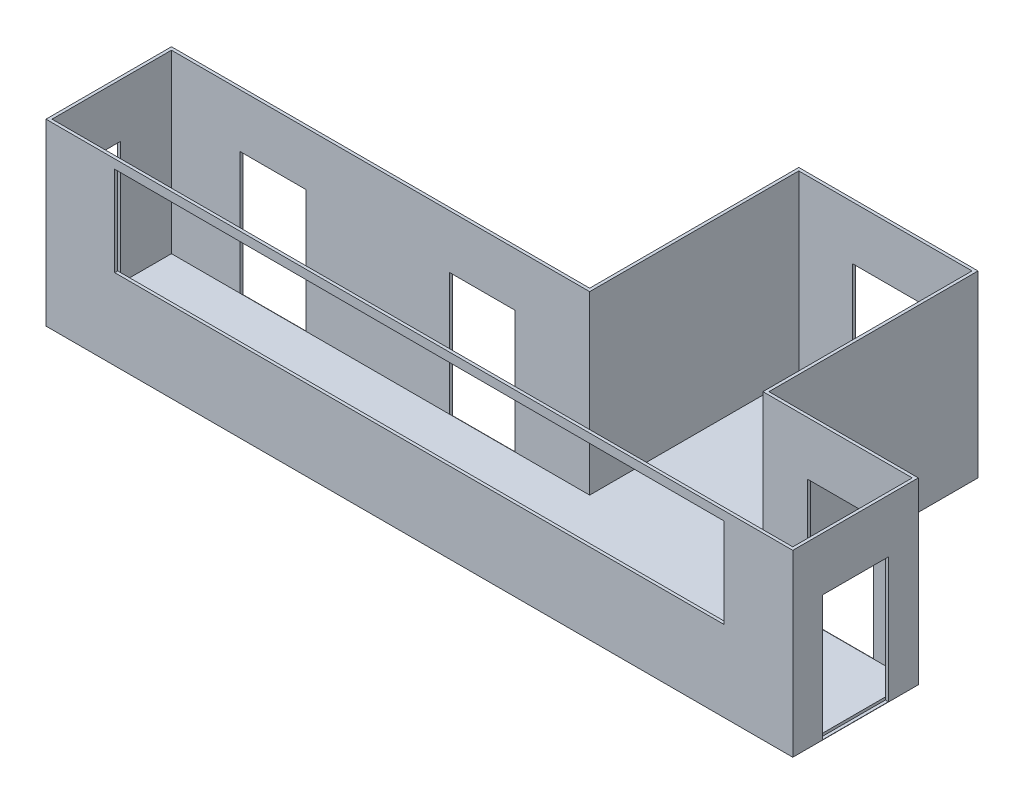
SolidWorks part; units mm, degrees
ref_plane "Front Plane" through (0, 0, 0) normal (0, 0, 1) x (1, 0, 0)
ref_plane "Top Plane" through (0, 0, 0) normal (0, 1, 0) x (1, 0, 0)
ref_plane "Right Plane" through (0, 0, 0) normal (1, 0, 0) x (0, 0, -1)
sketch "Sketch1" plane through (0, 0, 0) normal (0, 1, 0) x (1, 0, 0)
  line L0 (4377.6371, 49.5781) -> (6877.6371, 49.5781)
  line L1 (-5622.3629, 49.5781) -> (1377.6371, 49.5781)
  line L2 (-5622.3629, 49.5781) -> (-5622.3629, -2050.4219)
  line L3 (-5622.3629, -2050.4219) -> (6877.6371, -2050.4219)
  line L4 (6877.6371, 49.5781) -> (6877.6371, -2050.4219)
  line L5 (-5622.3629, 49.5781) -> (6877.6371, -2050.4219) construction
  line L6 (-5622.3629, -2050.4219) -> (6877.6371, 49.5781) construction
  line L7 (1377.6371, 3549.5781) -> (4377.6371, 3549.5781)
  line L8 (1377.6371, 3549.5781) -> (1377.6371, 49.5781)
  line L10 (4377.6371, 3549.5781) -> (4377.6371, 49.5781)
  line L11 (1377.6371, 3549.5781) -> (4377.6371, 49.5781) construction
  line L12 (1377.6371, 49.5781) -> (4377.6371, 3549.5781) construction
  point P4 (627.6371, -1000.4219)
  point P9 (2877.6371, 1799.5781)
  dimension "D1" = 12500
  dimension "D2" = 2100
  dimension "D3" = 7000
  dimension "D4" = 3000
  dimension "D5" = 3500
extrude "Boss-Extrude1" add sketch "Sketch1" along normal blind 3000
shell "Shell1" thickness 50
sketch "Sketch2" plane through (-5622.3629, 0, 0) normal (-1, 0, 0) x (0, 0, 1)
  line L0 (2050.4219, 3000) -> (2050.4219, 0) construction
  line L1 (850.4219, 2105) -> (1950.4219, 2105)
  line L2 (850.4219, 2105) -> (850.4219, 5)
  line L3 (850.4219, 5) -> (1950.4219, 5)
  line L4 (1950.4219, 2105) -> (1950.4219, 5)
  line L5 (850.4219, 2105) -> (1950.4219, 5) construction
  line L6 (850.4219, 5) -> (1950.4219, 2105) construction
  line L7 (-49.5781, 0) -> (2050.4219, 0) construction
  point P4 (1400.4219, 1055)
  dimension "D1" = 1100
  dimension "D2" = 100
  dimension "D3" = 2100
  dimension "D4" = 2105
extrude "Cut-Extrude1" cut sketch "Sketch2" against normal blind 50
sketch "Sketch3" plane through (0, 0, -49.5781) normal (0, 0, -1) x (-1, 0, 0)
  line L0 (5622.3629, 3000) -> (2122.3629, 3000)
  line L1 (-1377.6371, 3000) -> (5622.3629, 3000) construction
  line L2 (3872.3629, 3000) -> (3872.3629, 0) construction
  line L3 (-1377.6371, 0) -> (5622.3629, 0) construction
  line L4 (2122.3629, 3000) -> (-1377.6371, 3000)
  line L5 (4422.3629, 5) -> (3322.3629, 5)
  line L6 (4422.3629, 5) -> (4422.3629, 2105)
  line L7 (4422.3629, 2105) -> (3322.3629, 2105)
  line L8 (3322.3629, 5) -> (3322.3629, 2105)
  line L9 (4422.3629, 5) -> (3322.3629, 2105) construction
  line L10 (4422.3629, 2105) -> (3322.3629, 5) construction
  line L11 (372.3629, 3000) -> (372.3629, 0) construction
  line L13 (922.3629, 5) -> (-177.6371, 5)
  line L14 (922.3629, 5) -> (922.3629, 2105)
  line L15 (922.3629, 2105) -> (-177.6371, 2105)
  line L16 (-177.6371, 5) -> (-177.6371, 2105)
  line L17 (922.3629, 5) -> (-177.6371, 2105) construction
  line L18 (922.3629, 2105) -> (-177.6371, 5) construction
  point P9 (3872.3629, 1055)
  point P18 (372.3629, 1055)
  dimension "D1" = 3500
  dimension "D2" = 1100
  dimension "D3" = 2100
  dimension "D4" = 2105
  dimension "D5" = 2100
  dimension "D6" = 2105
  dimension "D7" = 1100
extrude "Cut-Extrude2" cut sketch "Sketch3" against normal blind 50 contours L16 L13 L14 L15 | L8 L5 L6 L7
sketch "Sketch4" plane through (0, 0, -3549.5781) normal (0, 0, -1) x (-1, 0, 0)
  line L0 (-2877.6371, 3000) -> (-2877.6371, 0) construction
  line L1 (-4377.6371, 3000) -> (-1377.6371, 3000) construction
  line L2 (-4377.6371, 0) -> (-1377.6371, 0) construction
  line L4 (-2327.6371, 5) -> (-3427.6371, 5)
  line L5 (-2327.6371, 5) -> (-2327.6371, 2105)
  line L6 (-2327.6371, 2105) -> (-3427.6371, 2105)
  line L7 (-3427.6371, 5) -> (-3427.6371, 2105)
  line L8 (-2327.6371, 5) -> (-3427.6371, 2105) construction
  line L9 (-2327.6371, 2105) -> (-3427.6371, 5) construction
  point P6 (-2877.6371, 1055)
  dimension "D1" = 2100
  dimension "D2" = 1100
  dimension "D3" = 2105
extrude "Cut-Extrude3" cut sketch "Sketch4" against normal blind 50
sketch "Sketch5" plane through (0, 0, -49.5781) normal (0, 0, -1) x (-1, 0, 0)
  line L0 (-4377.6371, 3000) -> (-6877.6371, 3000)
  line L1 (-5627.6371, 3000) -> (-5627.6371, 0) construction
  line L2 (-6877.6371, 0) -> (-4377.6371, 0) construction
  line L4 (-5077.6371, 5) -> (-6177.6371, 5)
  line L5 (-5077.6371, 5) -> (-5077.6371, 2105)
  line L6 (-5077.6371, 2105) -> (-6177.6371, 2105)
  line L7 (-6177.6371, 5) -> (-6177.6371, 2105)
  line L8 (-5077.6371, 5) -> (-6177.6371, 2105) construction
  line L9 (-5077.6371, 2105) -> (-6177.6371, 5) construction
  point P8 (-5627.6371, 1055)
  dimension "D1" = 1100
  dimension "D2" = 2100
  dimension "D3" = 2105
extrude "Cut-Extrude4" cut sketch "Sketch5" against normal blind 50 contours L7 L4 L5 L6
sketch "Sketch6" plane through (0, 0, 2050.4219) normal (0, 0, 1) x (1, 0, 0)
  line L0 (627.6371, 0) -> (627.6371, 3000) construction
  line L1 (-4472.3629, 2850) -> (627.6371, 2850)
  line L2 (-4472.3629, 2850) -> (-4472.3629, 1350)
  line L3 (-4472.3629, 1350) -> (627.6371, 1350)
  line L4 (627.6371, 2850) -> (627.6371, 1350)
  line L5 (-4472.3629, 2850) -> (627.6371, 1350) construction
  line L6 (-4472.3629, 1350) -> (627.6371, 2850) construction
  line L7 (627.6371, 2850) -> (5727.6371, 2850)
  line L8 (627.6371, 2850) -> (627.6371, 1350)
  line L9 (627.6371, 1350) -> (5727.6371, 1350)
  line L10 (5727.6371, 2850) -> (5727.6371, 1350)
  line L11 (627.6371, 2850) -> (5727.6371, 1350) construction
  line L12 (627.6371, 1350) -> (5727.6371, 2850) construction
  line L13 (-5622.3629, 0) -> (6877.6371, 0) construction
  line L14 (-5622.3629, 3000) -> (6877.6371, 3000) construction
  point P4 (-1922.3629, 2100)
  point P7 (3177.6371, 2100)
  dimension "D1" = 1500
  dimension "D2" = 5100
  dimension "D3" = 5100
  dimension "D4" = 150
extrude "Cut-Extrude5" cut sketch "Sketch6" against normal blind 50 contours L4 L1 L2 L3 | L10 L7 L4 L9
sketch "Sketch7" plane through (0, 0, -49.5781) normal (0, 0, -1) x (-1, 0, 0)
sketch "Sketch8" plane through (6877.6371, 0, 0) normal (1, 0, 0) x (0, 0, -1)
  line L0 (-2050.4219, 3000) -> (49.5781, 3000)
  line L1 (-450.4219, 5) -> (-1550.4219, 5)
  line L2 (-450.4219, 5) -> (-450.4219, 2105)
  line L3 (-450.4219, 2105) -> (-1550.4219, 2105)
  line L4 (-1550.4219, 5) -> (-1550.4219, 2105)
  line L5 (-450.4219, 5) -> (-1550.4219, 2105) construction
  line L6 (-450.4219, 2105) -> (-1550.4219, 5) construction
  line L7 (-1000.4219, 3000) -> (-1000.4219, -270.5246) construction
  line L8 (-2050.4219, 0) -> (49.5781, 0) construction
  point P0 (-1000.4219, 1055)
  dimension "D1" = 1100
  dimension "D2" = 2100
  dimension "D3" = 2105
extrude "Cut-Extrude6" cut sketch "Sketch8" against normal blind 50 contours L4 L1 L2 L3
